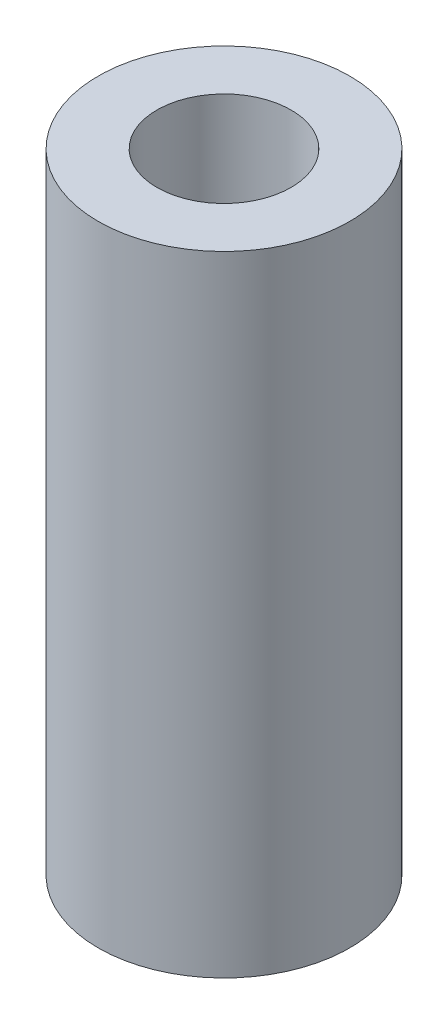
SolidWorks part; units mm, degrees
ref_plane "前基準面" through (0, 0, 0) normal (0, 0, 1) x (1, 0, 0)
ref_plane "上基準面" through (0, 0, 0) normal (0, 1, 0) x (1, 0, 0)
ref_plane "右基準面" through (0, 0, 0) normal (1, 0, 0) x (0, 0, -1)
sketch "草圖1" plane through (0, 0, 0) normal (0, 1, 0) x (1, 0, 0)
  circle A0 centre (0, 0) radius 1.6
  circle A1 centre (0, 0) radius 3
  dimension "D1" = 3.2
  dimension "D2" = 6
extrude "填料-伸長1" add sketch "草圖1" along normal blind 15
